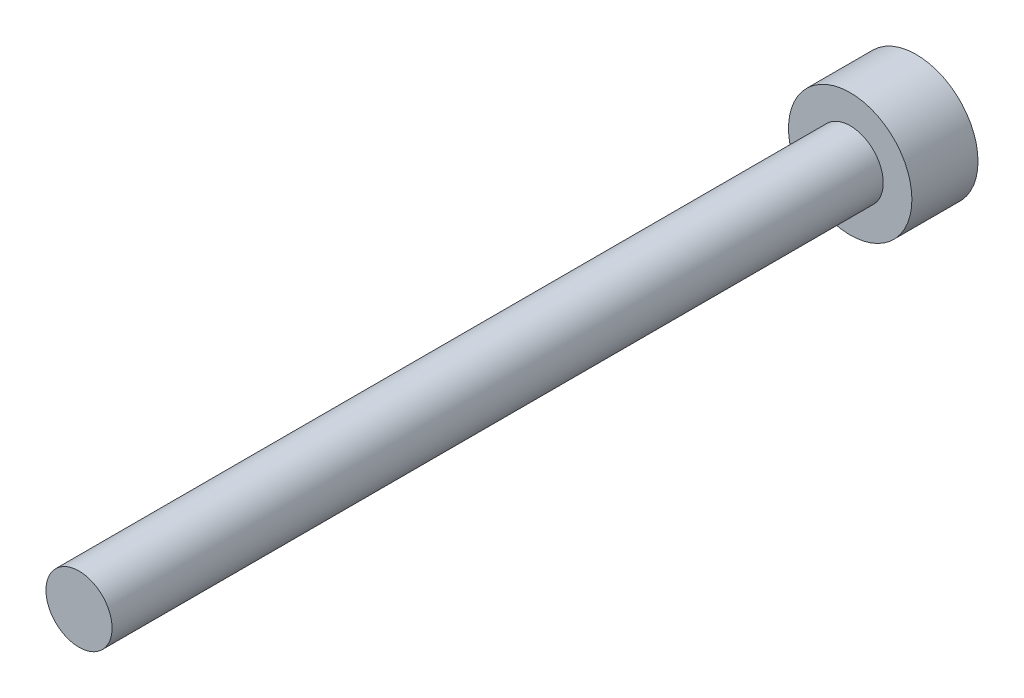
SolidWorks part; units mm, degrees
ref_plane "前视基准面" through (0, 0, 0) normal (0, 0, 1) x (1, 0, 0)
ref_plane "上视基准面" through (0, 0, 0) normal (0, 1, 0) x (1, 0, 0)
ref_plane "右视基准面" through (0, 0, 0) normal (1, 0, 0) x (0, 0, -1)
other "Configuration Table"
sketch "草图1" plane through (0, 0, 0) normal (0, 0, 1) x (1, 0, 0)
  circle A0 centre (0, 0) radius 2.8
  dimension "D1" = 5.6
extrude "凸台-拉伸1" add sketch "草图1" along normal blind 3
sketch "草图2" plane through (0, 0, 3) normal (0, 0, 1) x (1, 0, 0)
  circle A0 centre (0, 0) radius 1.5
  dimension "D1" = 3
extrude "凸台-拉伸2" add sketch "草图2" along normal blind 35
